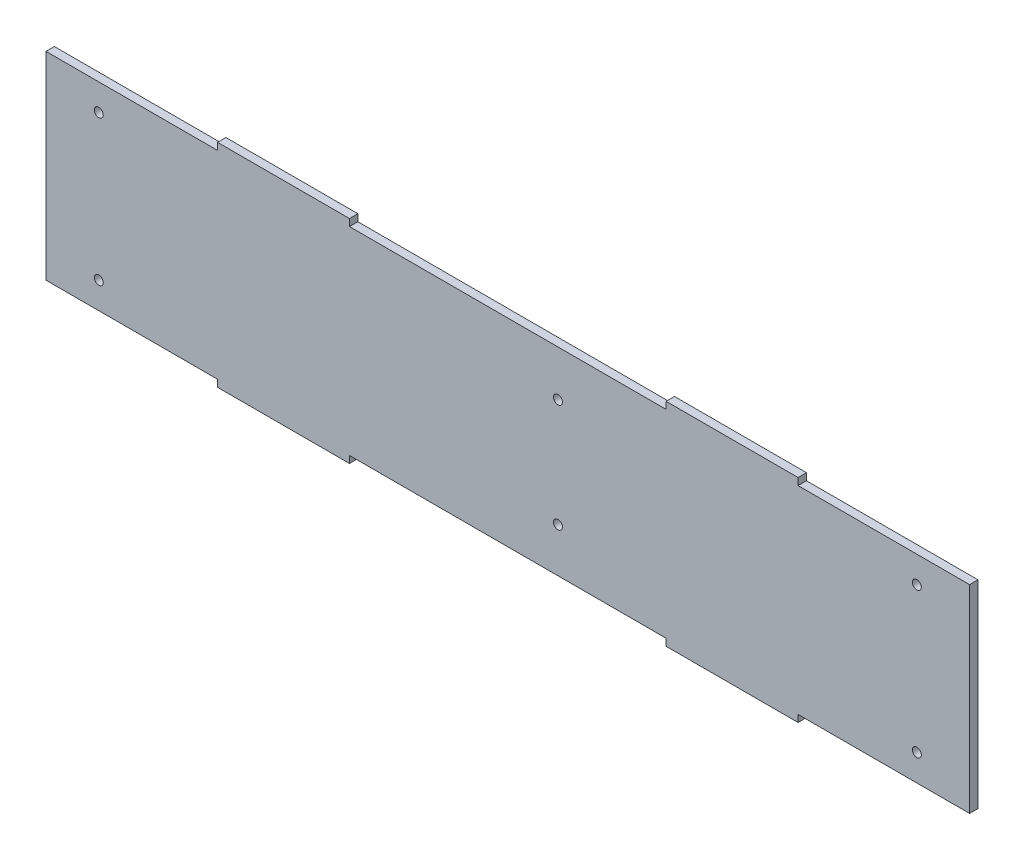
SolidWorks part; units mm, degrees
ref_plane "Front Plane" through (0, 0, 0) normal (0, 0, 1) x (1, 0, 0)
ref_plane "Top Plane" through (0, 0, 0) normal (0, 1, 0) x (1, 0, 0)
ref_plane "Right Plane" through (0, 0, 0) normal (1, 0, 0) x (0, 0, -1)
sketch "Sketch2" plane through (0, 0, 0) normal (0, 0, 1) x (1, 0, 0)
  line L0 (0, 0) -> (65, 0)
  line L1 (0, 0) -> (350, 0) construction
  line L2 (0, 0) -> (0, 75.1) construction
  line L3 (0, 75.1) -> (350, 75.1) construction
  line L4 (350, 0) -> (350, 75.1) construction
  line L5 (65, 0) -> (65, -2.65)
  line L6 (65, -2.65) -> (115, -2.65)
  line L7 (115, -2.65) -> (115, 0)
  line L8 (115, 0) -> (235, 0)
  line L9 (235, 0) -> (235, -2.65)
  line L10 (235, -2.65) -> (285, -2.65)
  line L11 (285, -2.65) -> (285, 0)
  line L12 (285, 0) -> (350, 0)
  line L13 (350, 0) -> (350, 75.1)
  line L14 (350, 75.1) -> (285, 75.1)
  line L15 (285, 75.1) -> (285, 77.75)
  line L16 (285, 77.75) -> (235, 77.75)
  line L17 (235, 77.75) -> (235, 75.1)
  line L18 (235, 75.1) -> (115, 75.1)
  line L19 (115, 75.1) -> (115, 77.75)
  line L20 (115, 77.75) -> (65, 77.75)
  line L21 (65, 77.75) -> (65, 75.1)
  line L22 (65, 75.1) -> (0, 75.1)
  line L23 (0, 75.1) -> (0, 0)
  line L24 (20, 10.05) -> (330, 10.05) construction
  line L25 (20, 65.05) -> (20, 10.05) construction
  line L26 (330, 10.05) -> (330, 65.05) construction
  line L27 (330, 65.05) -> (20, 65.05) construction
  circle A0 centre (20, 10.05) radius 1.7
  circle A1 centre (330, 10.05) radius 1.7
  circle A2 centre (330, 65.05) radius 1.7
  circle A3 centre (20, 65.05) radius 1.7
  circle A4 centre (194, 16.8) radius 1.7
  circle A5 centre (194, 57.8) radius 1.7
  point P23 (330, 64.7246)
  dimension "D6" = 3.4
  dimension "D1" = 2.65
  dimension "D2" = 75.1
  dimension "D3" = 350
  dimension "D4" = 50
  dimension "D5" = 65
  dimension "D7" = 10.05
  dimension "D8" = 20
  dimension "D9" = 10.05
  dimension "D10" = 20
extrude "Boss-Extrude1" add sketch "Sketch2" along normal blind 3.175
